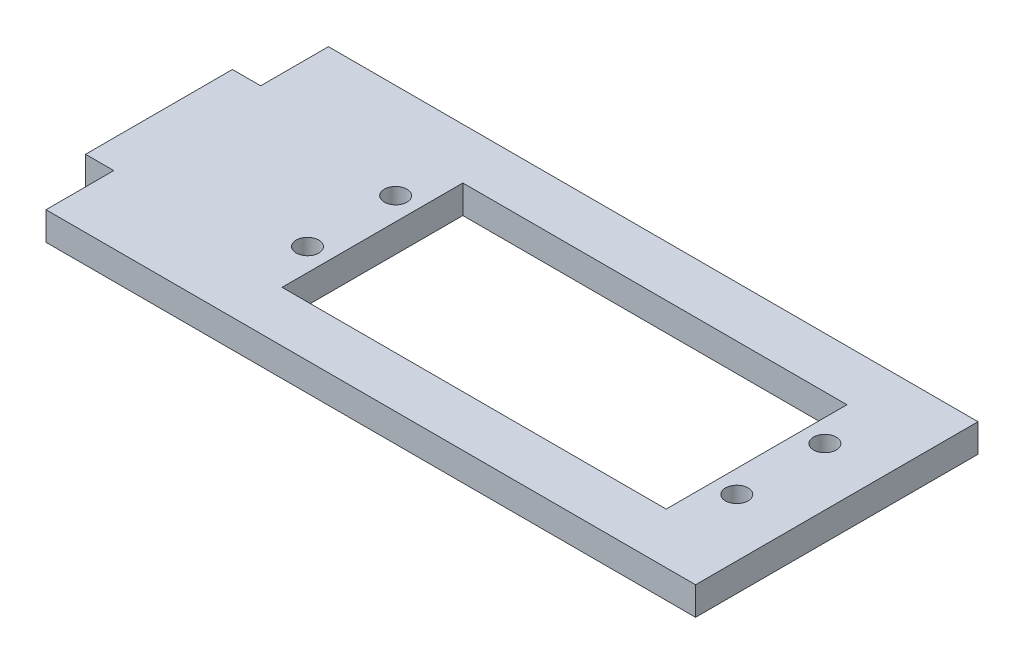
SolidWorks part; units mm, degrees
ref_plane "Front Plane" through (0, 0, 0) normal (0, 0, 1) x (1, 0, 0)
ref_plane "Top Plane" through (0, 0, 0) normal (0, 1, 0) x (1, 0, 0)
ref_plane "Right Plane" through (0, 0, 0) normal (1, 0, 0) x (0, 0, -1)
sketch "Sketch1" plane through (0, 0, 0) normal (0, 1, 0) x (1, 0, 0)
  line L0 (-32.6945, 18.2399) -> (43.5055, 18.2399)
  line L1 (-32.6945, 18.2399) -> (-32.6945, -13.5101)
  line L2 (-32.6945, -13.5101) -> (43.5055, -13.5101)
  line L3 (43.5055, 18.2399) -> (43.5055, -13.5101)
  line L4 (-32.6945, 18.2399) -> (43.5055, -13.5101) construction
  line L5 (-32.6945, -13.5101) -> (43.5055, 18.2399) construction
  point P0 (5.4055, 2.3649)
  dimension "D1" = 31.75
  dimension "D2" = 76.2
extrude "Boss-Extrude1" add sketch "Sketch1" along normal blind 3.175
sketch "Sketch2" plane through (0, 3.175, 0) normal (0, 1, 0) x (1, 0, 0)
  line L0 (43.5055, 2.3649) -> (-32.6945, 2.3649) construction
  line L1 (-32.6945, 18.2399) -> (-29.5195, 18.2399)
  line L2 (-32.6945, 18.2399) -> (-32.6945, 10.6199)
  line L3 (-32.6945, 10.6199) -> (-29.5195, 10.6199)
  line L4 (-29.5195, 18.2399) -> (-29.5195, 10.6199)
  line L5 (-32.6945, -13.5101) -> (-29.5195, -13.5101)
  line L6 (-32.6945, -13.5101) -> (-32.6945, -5.8901)
  line L7 (-32.6945, -5.8901) -> (-29.5195, -5.8901)
  line L8 (-29.5195, -13.5101) -> (-29.5195, -5.8901)
  line L9 (43.5055, -13.5101) -> (43.5055, 18.2399) construction
  line L10 (-32.6945, 18.2399) -> (-32.6945, -13.5101) construction
  line L11 (-11.2327, 7.5084) -> (-11.2327, -2.3976) construction
  line L12 (-8.6927, 12.5249) -> (34.4873, 12.5249)
  line L13 (-8.6927, 12.5249) -> (-8.6927, -7.7951)
  line L14 (-8.6927, -7.7951) -> (34.4873, -7.7951)
  line L15 (34.4873, 12.5249) -> (34.4873, -7.7951)
  line L16 (-8.6927, 12.5249) -> (34.4873, -7.7951) construction
  line L17 (-8.6927, -7.7951) -> (34.4873, 12.5249) construction
  line L18 (12.8973, -7.7951) -> (12.8973, 12.5249) construction
  circle A0 centre (37.0273, 7.5084) radius 1.27
  circle A1 centre (37.0273, -2.3976) radius 1.27
  circle A2 centre (-11.2327, 7.5084) radius 1.27
  circle A3 centre (-11.2327, -2.3976) radius 1.27
  point P17 (12.8973, 2.3649)
  dimension "D6" = 9.906
  dimension "D1" = 3.175
  dimension "D2" = 7.62
  dimension "D3" = 7.62
  dimension "D4" = 20.32
  dimension "D5" = 43.18
  dimension "D7" = 4.7625
  dimension "D8" = 4.7625
  dimension "D9" = 9.906
  dimension "D10" = 48.26
  dimension "D11" = 48.26
  dimension "D12" = 24.13
  dimension "D13" = 3.175
extrude "Cut-Extrude1" cut sketch "Sketch2" against normal blind 3.175
